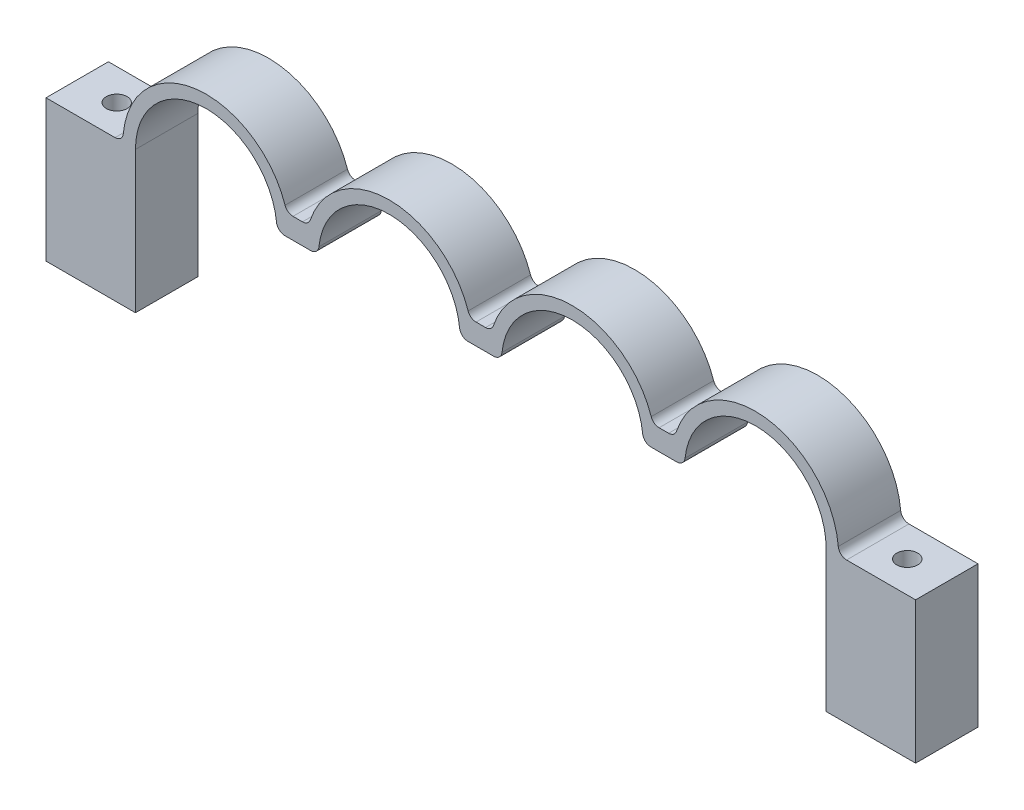
SolidWorks part; units mm, degrees
ref_plane "前视基准面" through (0, 0, 0) normal (0, 0, 1) x (1, 0, 0)
ref_plane "上视基准面" through (0, 0, 0) normal (0, 1, 0) x (1, 0, 0)
ref_plane "右视基准面" through (0, 0, 0) normal (1, 0, 0) x (0, 0, -1)
sketch "草图1" plane through (0, 0, 0) normal (0, 0, 1) x (1, 0, 0)
  line L0 (-20, 0) -> (-17, 0)
  line L1 (17, 0) -> (20, 0)
  arc A0 (17, 0) -> (-17, 0) centre (0, 0) ccw
  arc A1 (20, 0) -> (-20, 0) centre (0, 0) ccw
  dimension "D1" = 34
  dimension "D2" = 40
extrude "凸台-拉伸1" add sketch "草图1" along normal blind 15
sketch "草图2" plane through (0, 0, 15) normal (0, 0, 1) x (1, 0, 0)
  line L0 (-27, 0) -> (-17, 0) construction
  line L1 (-61, 0) -> (-64, 0) construction
  line L2 (-105, 0) -> (-108, 0) construction
  line L3 (-152, 0) -> (-149, 0)
  line L4 (-115, 0) -> (-112, 0)
  line L5 (-71, 0) -> (-68, 0)
  line L6 (-27, 0) -> (-24, 0)
  line L7 (-68, 0) -> (-71, 0) construction
  line L8 (-64, 0) -> (-61, 0)
  line L9 (-112, 0) -> (-115, 0) construction
  line L10 (-108, 0) -> (-105, 0)
  arc A0 (-27, 0) -> (-61, 0) centre (-44, 0) ccw
  arc A1 (-24, 0) -> (-64, 0) centre (-44, 0) ccw
  arc A2 (-71, 0) -> (-105, 0) centre (-88, 0) ccw
  arc A3 (-68, 0) -> (-108, 0) centre (-88, 0) ccw
  arc A4 (-115, 0) -> (-149, 0) centre (-132, 0) ccw
  arc A5 (-112, 0) -> (-152, 0) centre (-132, 0) ccw
  dimension "D1" = 34
  dimension "D3" = 40
  dimension "D2" = 10
  dimension "D4" = 10
  dimension "D5" = 10
extrude "凸台-拉伸2" add sketch "草图2" against normal blind 15 separate body
sketch "草图3" plane through (0, 0, 0) normal (0, -1, 0) x (1, 0, 0)
  line L0 (-115, 15) -> (-112, 15) construction
  line L1 (-113.5, 15) -> (-106.5, 15)
  line L2 (-113.5, 15) -> (-113.5, 0)
  line L3 (-113.5, 0) -> (-106.5, 0)
  line L4 (-106.5, 15) -> (-106.5, 0)
  line L5 (-108, 0) -> (-105, 0) construction
  line L6 (-71, 15) -> (-68, 15) construction
  line L7 (-69.5, 15) -> (-62.5, 15)
  line L8 (-69.5, 15) -> (-69.5, 0)
  line L9 (-69.5, 0) -> (-62.5, 0)
  line L10 (-62.5, 15) -> (-62.5, 0)
  line L11 (-64, 0) -> (-61, 0) construction
  line L12 (-27, 15) -> (-24, 15) construction
  line L13 (-25.5, 15) -> (-18.5, 15)
  line L14 (-25.5, 15) -> (-25.5, 0)
  line L15 (-25.5, 0) -> (-18.5, 0)
  line L16 (-18.5, 15) -> (-18.5, 0)
  line L17 (-20, 0) -> (-17, 0) construction
extrude "凸台-拉伸3" add sketch "草图3" against normal blind 5
sketch "草图4" plane through (0, 0, 0) normal (0, -1, 0) x (1, 0, 0)
  line L1 (17, 15) -> (57, 15)
  line L2 (17, 15) -> (17, 0)
  line L3 (17, 0) -> (57, 0)
  line L4 (57, 15) -> (57, 0)
  line L5 (-149, 15) -> (-189, 15)
  line L6 (-149, 15) -> (-149, 0)
  line L7 (-149, 0) -> (-189, 0)
  line L8 (-189, 15) -> (-189, 0)
  dimension "D1" = 40
  dimension "D2" = 40
  dimension "D3" = 15
  dimension "D4" = 15
extrude "凸台-拉伸4" add sketch "草图4" along normal blind 34
sketch "草图6" plane through (0, 0, 0) normal (0, 1, 0) x (1, 0, 0)
  line L0 (57, 0) -> (57, -15) construction
  line L1 (-189, -15) -> (-189, 0) construction
  circle A0 centre (29, -7.5) radius 2.5
  circle A1 centre (-161, -7.5) radius 2.5
  point P7 (57, -7.5)
  dimension "D1" = 5
  dimension "D2" = 5
  dimension "D3" = 28
  dimension "D4" = 28
extrude "切除-拉伸2" cut sketch "草图6" against normal blind 34
sketch "草图7" plane through (0, 0, 0) normal (0, 1, 0) x (1, 0, 0)
  line L0 (-152, -15) -> (-189, -15) construction
  line L1 (-189, 0) -> (-170.5, 0)
  line L2 (-189, 0) -> (-189, -15)
  line L3 (-189, -15) -> (-170.5, -15)
  line L4 (-170.5, 0) -> (-170.5, -15)
  line L5 (-66, -15) -> (-66, -43.9577) construction
  line L6 (-63.3649, -15) -> (-68.6351, -15) construction
  line L7 (38.5, 0) -> (38.5, -15)
  line L8 (57, -15) -> (38.5, -15)
  line L9 (57, 0) -> (57, -15)
  line L10 (57, 0) -> (38.5, 0)
extrude "切除-拉伸3" cut sketch "草图7" against normal blind 100
fillet "圆角1" radius 2 8 edges at (20, 0, 7.5) (-19.3649, 5, 7.5) (-24.6351, 5, 7.5) (-68.6351, 5, 7.5) (-63.3649, 5, 7.5) (-107.3649, 5, 7.5) (-112.6351, 5, 7.5) (-152, 0, 7.5)
fillet "圆角2" radius 2 6 edges at (-17, 0, 7.5) (-27, 0, 7.5) (-61, 0, 7.5) (-71, 0, 7.5) (-105, 0, 7.5) (-115, 0, 7.5)
